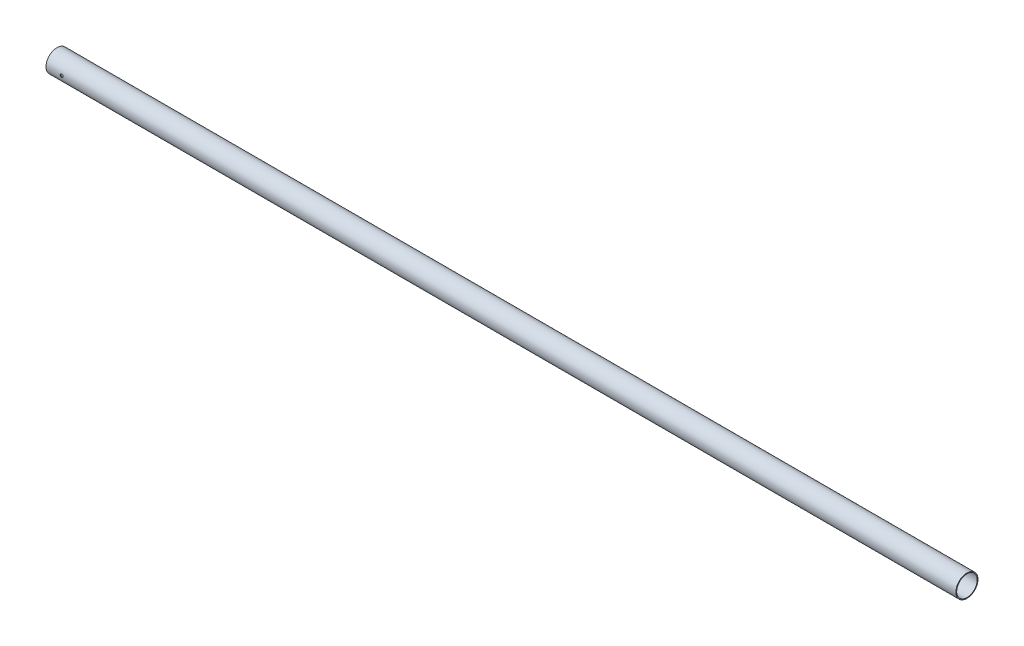
SolidWorks part; units mm, degrees
ref_plane "Front Plane" through (0, 0, 0) normal (0, 0, 1) x (1, 0, 0)
ref_plane "Top Plane" through (0, 0, 0) normal (0, 1, 0) x (1, 0, 0)
ref_plane "Right Plane" through (0, 0, 0) normal (1, 0, 0) x (0, 0, -1)
sketch "Sketch1" plane through (0, 0, 0) normal (1, 0, 0) x (0, 0, -1)
  circle A0 centre (0, 0) radius 12.7
  circle A1 centre (0, 0) radius 11.811
extrude "Boss-Extrude1" add sketch "Sketch1" along normal blind 1045.96
sketch "Sketch2" plane through (0, 0, 0) normal (0, 0, 1) x (1, 0, 0)
  circle A0 centre (18, 0) radius 1.7
extrude "Cut-Extrude1" cut sketch "Sketch2" against normal through all and the other way through all
